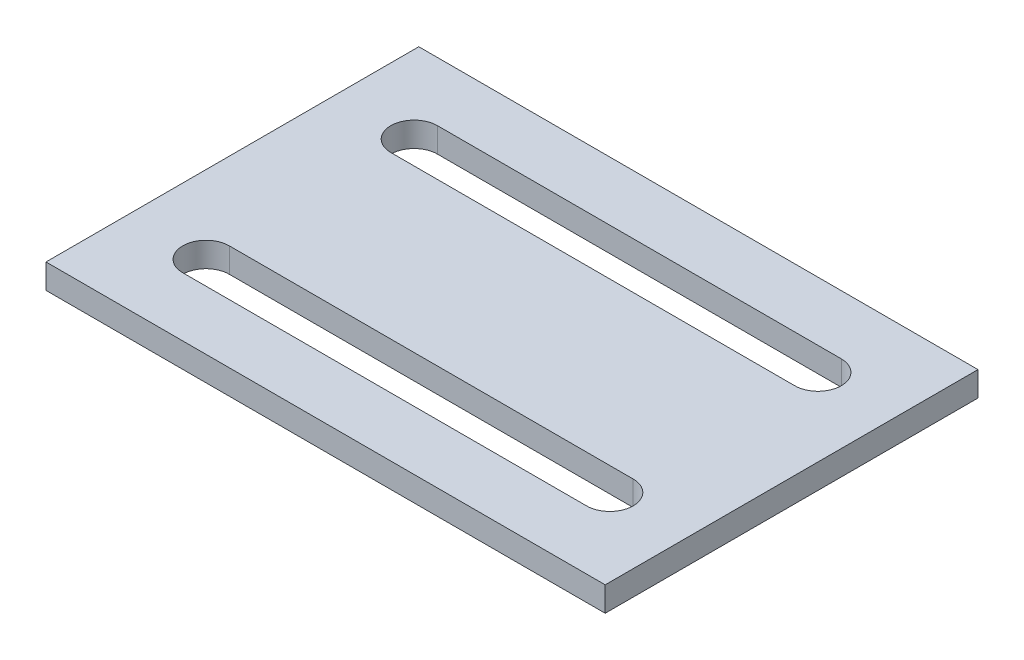
SolidWorks part; units mm, degrees
ref_plane "Alzado" through (0, 0, 0) normal (0, 0, 1) x (1, 0, 0)
ref_plane "Planta" through (0, 0, 0) normal (0, 1, 0) x (1, 0, 0)
ref_plane "Vista lateral" through (0, 0, 0) normal (1, 0, 0) x (0, 0, -1)
sketch "Croquis1" plane through (0, 0, 0) normal (0, 1, 0) x (1, 0, 0)
  line L0 (-90, -33.5) -> (90, -33.5) construction
  line L1 (90, -60) -> (-90, -60)
  line L2 (90, -60) -> (90, 60)
  line L3 (90, 60) -> (-90, 60)
  line L4 (-90, -60) -> (-90, 60)
  line L5 (90, -60) -> (-90, 60) construction
  line L6 (90, 60) -> (-90, -60) construction
  line L7 (-90, 33.5) -> (90, 33.5) construction
  line L8 (-65, -33.5) -> (65, -33.5) construction
  line L9 (-65, -26) -> (65, -26)
  line L10 (-65, -41) -> (65, -41)
  line L11 (-65, 33.5) -> (65, 33.5) construction
  line L12 (-65, 41) -> (65, 41)
  line L13 (-65, 26) -> (65, 26)
  arc A0 (-65, -26) -> (-65, -41) centre (-65, -33.5) ccw
  arc A1 (65, -41) -> (65, -26) centre (65, -33.5) ccw
  arc A2 (-65, 41) -> (-65, 26) centre (-65, 33.5) ccw
  arc A3 (65, 26) -> (65, 41) centre (65, 33.5) ccw
  point P0 (0, 0)
  point P12 (0, -33.5)
  point P19 (0, 33.5)
  dimension "D5" = 7.5
  dimension "D7" = 7.5
  dimension "D1" = 120
  dimension "D2" = 180
  dimension "D3" = 67
  dimension "D4" = 33.5
  dimension "D6" = 130
extrude "Saliente-Extruir1" add sketch "Croquis1" along normal blind 7.9375
